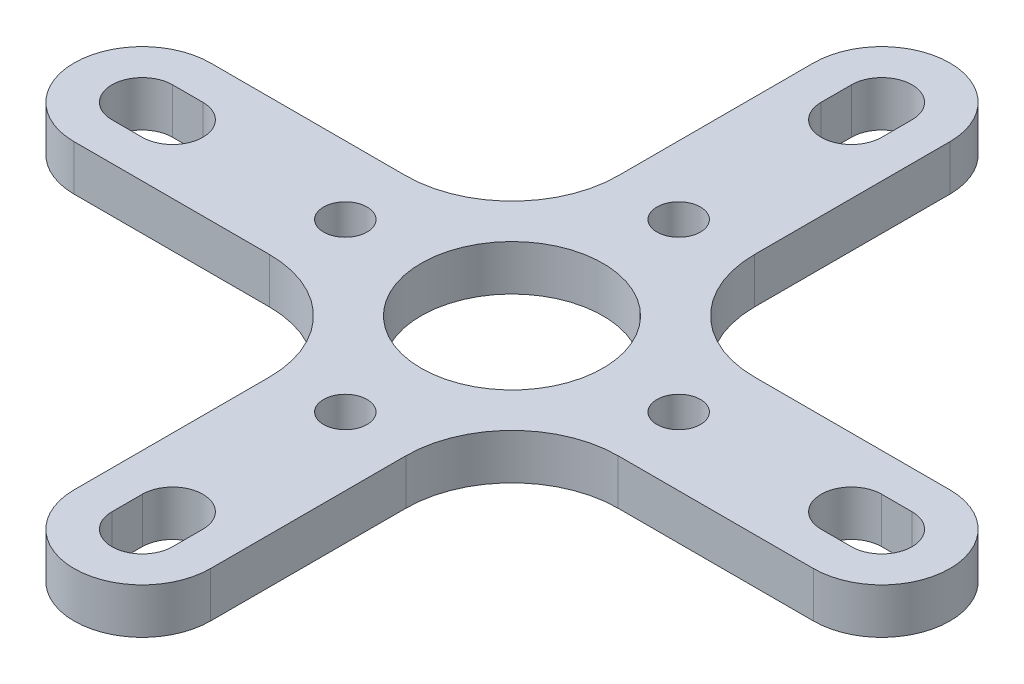
SolidWorks part; units mm, degrees
material "AISI 1020"
ref_plane "Front Plane" through (0, 0, 0) normal (0, 0, 1) x (1, 0, 0)
ref_plane "Top Plane" through (0, 0, 0) normal (0, 1, 0) x (1, 0, 0)
ref_plane "Right Plane" through (0, 0, 0) normal (1, 0, 0) x (0, 0, -1)
sketch "Sketch1" plane through (0, 0, 0) normal (0, 1, 0) x (1, 0, 0)
  line L0 (0, 24.4) -> (0, -24.4) construction
  line L1 (4.5, 24.4) -> (4.5, -24.4)
  line L2 (-4.5, 24.4) -> (-4.5, -24.4)
  line L3 (-24.4, 0) -> (24.4, 0) construction
  line L4 (-24.4, 4.5) -> (24.4, 4.5)
  line L5 (-24.4, -4.5) -> (24.4, -4.5)
  arc A0 (4.5, 24.4) -> (-4.5, 24.4) centre (0, 24.4) ccw
  arc A1 (-4.5, -24.4) -> (4.5, -24.4) centre (0, -24.4) ccw
  arc A2 (-24.4, 4.5) -> (-24.4, -4.5) centre (-24.4, 0) ccw
  arc A3 (24.4, -4.5) -> (24.4, 4.5) centre (24.4, 0) ccw
  point P2 (0, 0)
  point P10 (0, 0)
  point P15 (-28.9, 0)
  point P16 (28.9, 0)
  dimension "D1" = 57.8
  dimension "D2" = 9
extrude "Boss-Extrude1" add sketch "Sketch1" along normal blind 3 contours L2 A1 L1 L5 | L2 L5 L1 L4 | L5 A3 L4 L1 | L1 A0 L2 L4 | L4 A2 L5 L2
sketch "Sketch2" plane through (0, 3, 0) normal (0, 1, 0) x (1, 0, 0)
  circle A0 centre (0, 0) radius 6
  dimension "D1" = 12
fillet "Fillet1" radius 7 4 edges at (-4.5, 1.5, 4.5) (4.5, 1.5, 4.5) (4.5, 1.5, -4.5) (-4.5, 1.5, -4.5)
extrude "Cut-Extrude1" cut sketch "Sketch2" against normal through all
sketch "Sketch5" plane through (0, 3, 0) normal (0, 1, 0) x (1, 0, 0)
  circle A0 centre (-11, 0) radius 1.4351 construction
  circle A1 centre (0, 11) radius 1.4351 construction
  circle A2 centre (11, 0) radius 1.4351 construction
  circle A3 centre (0, -11) radius 1.4351 construction
  circle A4 centre (-11, 0) radius 1.4351
  circle A5 centre (0, 11) radius 1.4351
  circle A6 centre (11, 0) radius 1.4351
  circle A7 centre (0, -11) radius 1.4351
extrude "Cut-Extrude2" cut sketch "Sketch5" against normal through all
sketch "Sketch6" plane through (0, 3, 0) normal (0, 1, 0) x (1, 0, 0)
  line L0 (-22.4, 0) -> (-24.4, 0) construction
  line L1 (-22.4, -2) -> (-24.4, -2)
  line L2 (-22.4, 2) -> (-24.4, 2)
  line L3 (0, 22.4) -> (0, 24.4) construction
  line L4 (-2, 22.4) -> (-2, 24.4)
  line L5 (2, 22.4) -> (2, 24.4)
  line L6 (22.4, 0) -> (24.4, 0) construction
  line L7 (22.4, 2) -> (24.4, 2)
  line L8 (22.4, -2) -> (24.4, -2)
  line L9 (0, -22.4) -> (0, -24.4) construction
  line L10 (2, -22.4) -> (2, -24.4)
  line L11 (-2, -22.4) -> (-2, -24.4)
  arc A0 (-22.4, -2) -> (-22.4, 2) centre (-22.4, 0) ccw
  arc A1 (-24.4, 2) -> (-24.4, -2) centre (-24.4, 0) ccw
  arc A2 (-2, 22.4) -> (2, 22.4) centre (0, 22.4) ccw
  arc A3 (2, 24.4) -> (-2, 24.4) centre (0, 24.4) ccw
  arc A4 (22.4, 2) -> (22.4, -2) centre (22.4, 0) ccw
  arc A5 (24.4, -2) -> (24.4, 2) centre (24.4, 0) ccw
  arc A6 (2, -22.4) -> (-2, -22.4) centre (0, -22.4) ccw
  arc A7 (-2, -24.4) -> (2, -24.4) centre (0, -24.4) ccw
  point P2 (-23.4, 0)
  point P8 (-26.4, 0)
  point P9 (-20.4, 0)
  point P10 (0, 0)
  point P11 (0, 0)
  point P12 (-24.4, 0)
  point P17 (0, 23.4)
  point P22 (0, 26.4)
  point P23 (0, 20.4)
  point P24 (0, 24.4)
  point P27 (23.4, 0)
  point P32 (26.4, 0)
  point P33 (20.4, 0)
  point P34 (24.4, 0)
  point P37 (0, -23.4)
  point P42 (0, -26.4)
  point P43 (0, -20.4)
  point P44 (0, -24.4)
  point P45 (0, 0)
  dimension "D1" = 4
  dimension "D2" = 6
  dimension "D3" = 4
extrude "Cut-Extrude3" cut sketch "Sketch6" against normal through all
